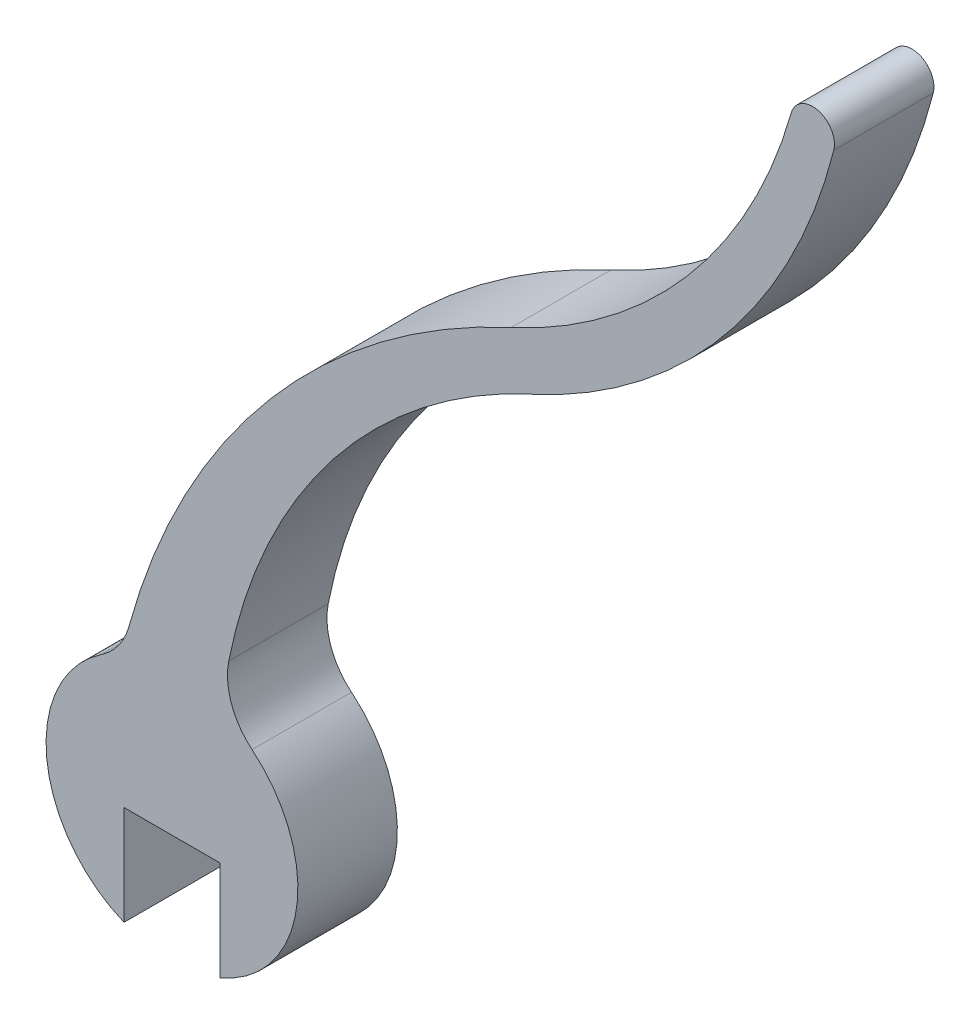
SolidWorks part; units mm, degrees
material "Acrylic (Medium-high impact)"
ref_plane "Front Plane" through (0, 0, 0) normal (0, 0, 1) x (1, 0, 0)
ref_plane "Top Plane" through (0, 0, 0) normal (0, 1, 0) x (1, 0, 0)
ref_plane "Right Plane" through (0, 0, 0) normal (1, 0, 0) x (0, 0, -1)
sketch "스케치1" plane through (0, 0, 0) normal (0, 0, 1) x (1, 0, 0)
  line L0 (-22.7032, -30.5347) -> (-19.8082, -30.5347) construction
  line L1 (-22.7032, -30.5347) -> (-22.7032, -27.5347)
  line L2 (-19.8082, -30.5347) -> (-19.8082, -27.5347)
  line L3 (-22.7032, -27.5347) -> (-19.8082, -27.5347)
  line L4 (-22.7032, -30.5347) -> (-19.8082, -27.5347) construction
  line L5 (-19.8082, -30.5347) -> (-22.7032, -27.5347) construction
  line L6 (-21.2557, -29.0347) -> (-21.2557, -27.0237) construction
  line L7 (-22.7557, -23.5347) -> (-19.7557, -23.5347) construction
  line L8 (-21.2557, -23.5347) -> (-21.2557, -27.0237) construction
  arc A0 (-22.7557, -23.5347) -> (-11.0258, -9.1602) centre (-2.2808, -28.2696) cw
  arc A1 (-11.0258, -9.1602) -> (-2.5758, 0.678) centre (-17.471, 4.9235) ccw
  circle A2 centre (-21.2557, -27.0237) radius 3.7977 construction
  arc A3 (-19.7557, -23.5347) -> (-10.4267, -10.6031) centre (-3.7644, -25.2402) cw
  arc A4 (-10.4267, -10.6031) -> (-1.2963, 0.334) centre (-17.2388, 4.3633) ccw
  arc A5 (-2.5758, 0.678) -> (-1.2963, 0.334) centre (-1.9386, 0.4964) cw
  arc A6 (-22.7557, -23.5347) -> (-22.7032, -30.5347) centre (-21.2557, -27.0237) ccw
  arc A7 (-19.7557, -23.5347) -> (-19.8082, -30.5347) centre (-21.2557, -27.0237) cw
  point P10 (-21.2557, -29.0347)
  dimension "D1" = 2.895
  dimension "D3" = 4
  dimension "D4" = 3
  dimension "D2" = 3
extrude "보스-돌출1" add sketch "스케치1" along normal blind 3
fillet "필렛1" radius 2.032 2 edges at (-22.7557, -23.5347, 1.5) (-19.7557, -23.5347, 1.5)
